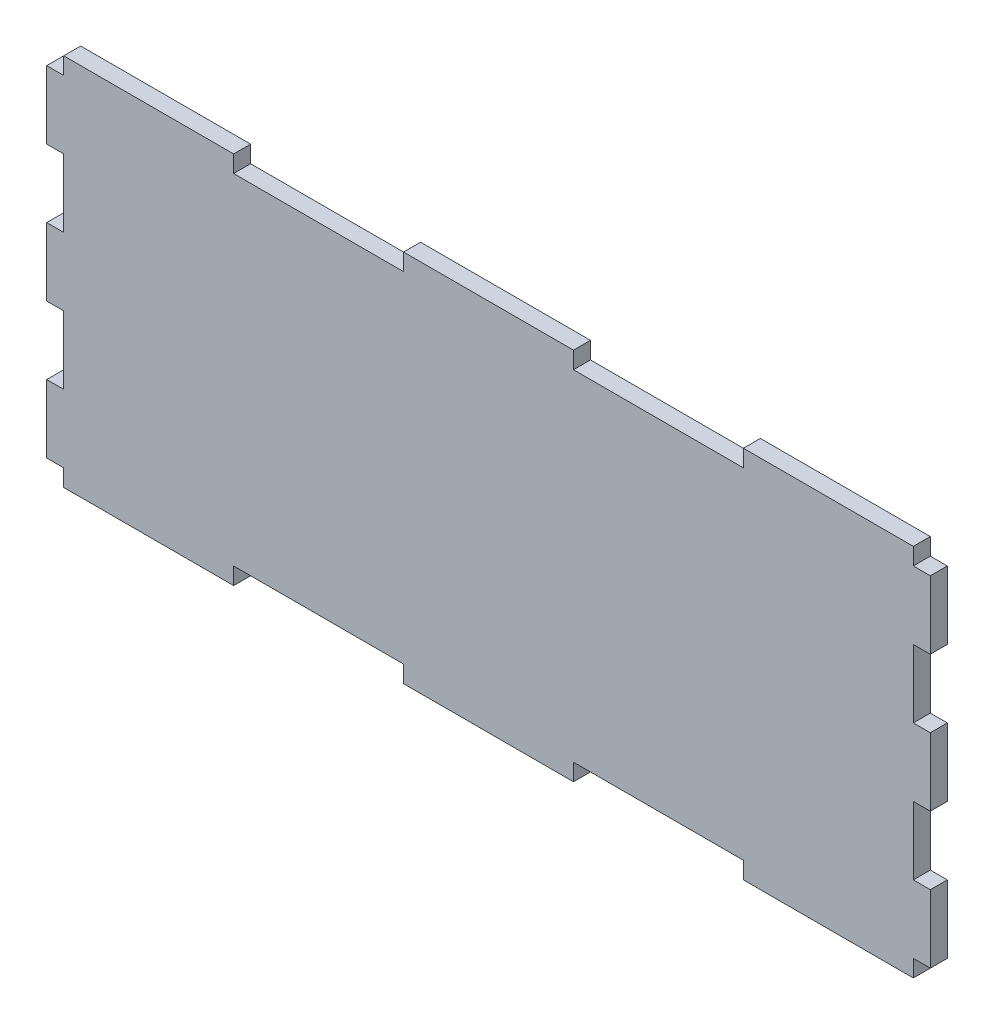
SolidWorks part; units mm, degrees
material "Pinho"
ref_plane "Plano frontal" through (0, 0, 0) normal (0, 0, 1) x (1, 0, 0)
ref_plane "Plano superior" through (0, 0, 0) normal (0, 1, 0) x (1, 0, 0)
ref_plane "Plano direito" through (0, 0, 0) normal (1, 0, 0) x (0, 0, -1)
sketch "Esboço1" plane through (0, 0, 0) normal (0, 0, 1) x (1, 0, 0)
  line L0 (-82.2996, 0) -> (-4.2219, 0) construction
  line L1 (40.7004, -30) -> (10.7004, -30)
  line L2 (70.7004, -18) -> (70.7004, -6)
  line L3 (40.7004, 30) -> (10.7004, 30)
  line L4 (-79.2996, -18) -> (-79.2996, -6)
  line L5 (70.7004, 6) -> (70.7004, 18)
  line L6 (-19.2996, 30) -> (-49.2996, 30)
  line L7 (-79.2996, 30) -> (-82.2996, 30)
  line L9 (-79.2996, 18) -> (-82.2996, 18)
  line L10 (-82.2996, 30) -> (-82.2996, 18)
  line L11 (-79.2996, -30) -> (-82.2996, -30)
  line L13 (-79.2996, -18) -> (-82.2996, -18)
  line L14 (-82.2996, -30) -> (-82.2996, -18)
  line L15 (-4.2219, 33) -> (-4.2219, 0) construction
  line L16 (-79.2996, 6) -> (-79.2996, 18)
  line L17 (-82.2996, -6) -> (-79.2996, -6)
  line L18 (-82.2996, -6) -> (-82.2996, 6)
  line L19 (-82.2996, 6) -> (-79.2996, 6)
  line L20 (70.7004, -6) -> (73.7004, -6)
  line L22 (70.7004, 6) -> (73.7004, 6)
  line L23 (73.7004, -6) -> (73.7004, 6)
  line L25 (-79.2996, 30) -> (-79.2996, 33)
  line L26 (70.7004, 30) -> (73.7004, 30)
  line L28 (70.7004, 18) -> (73.7004, 18)
  line L29 (73.7004, 30) -> (73.7004, 18)
  line L30 (70.7004, -30) -> (73.7004, -30)
  line L32 (70.7004, -18) -> (73.7004, -18)
  line L33 (73.7004, -30) -> (73.7004, -18)
  line L34 (-79.2996, 33) -> (-49.2996, 33)
  line L35 (-49.2996, 30) -> (-49.2996, 33)
  line L37 (70.7004, 30) -> (70.7004, 33)
  line L38 (70.7004, 33) -> (40.7004, 33)
  line L39 (40.7004, 30) -> (40.7004, 33)
  line L41 (-19.2996, 30) -> (-19.2996, 33)
  line L42 (-19.2996, 33) -> (10.7004, 33)
  line L43 (10.7004, 30) -> (10.7004, 33)
  line L44 (-19.2996, -30) -> (-49.2996, -30)
  line L46 (-19.2996, -30) -> (-19.2996, -33)
  line L47 (-19.2996, -33) -> (10.7004, -33)
  line L48 (10.7004, -30) -> (10.7004, -33)
  line L49 (-4.2219, 0) -> (73.7004, 0) construction
  line L50 (-4.2219, 0) -> (-4.2219, -33) construction
  line L52 (-79.2996, -30) -> (-79.2996, -33)
  line L53 (-79.2996, -33) -> (-49.2996, -33)
  line L54 (-49.2996, -30) -> (-49.2996, -33)
  line L56 (70.7004, -30) -> (70.7004, -33)
  line L57 (70.7004, -33) -> (40.7004, -33)
  line L58 (40.7004, -30) -> (40.7004, -33)
  point P0 (0, 0)
  point P44 (0, 0)
  point P51 (0, 0)
  dimension "D1" = 60
  dimension "D2" = 150
  dimension "D3" = 3
  dimension "D4" = 12
  dimension "D5" = 12
  dimension "D6" = 12
  dimension "D7" = 3
  dimension "D8" = 3
  dimension "D9" = 6
  dimension "D10" = 12
  dimension "D11" = 3
  dimension "D12" = 12
  dimension "D13" = 3
  dimension "D14" = 12
  dimension "D15" = 3
  dimension "D16" = 30
  dimension "D17" = 30
  dimension "D18" = 30
  dimension "D19" = 3
  dimension "D20" = 3
  dimension "D21" = 3
  dimension "D22" = 30
  dimension "D23" = 30
  dimension "D24" = 30
  dimension "D25" = 3
  dimension "D26" = 3
  dimension "D27" = 3
extrude "Ressalto-extrusão1" add sketch "Esboço1" along normal blind 3
